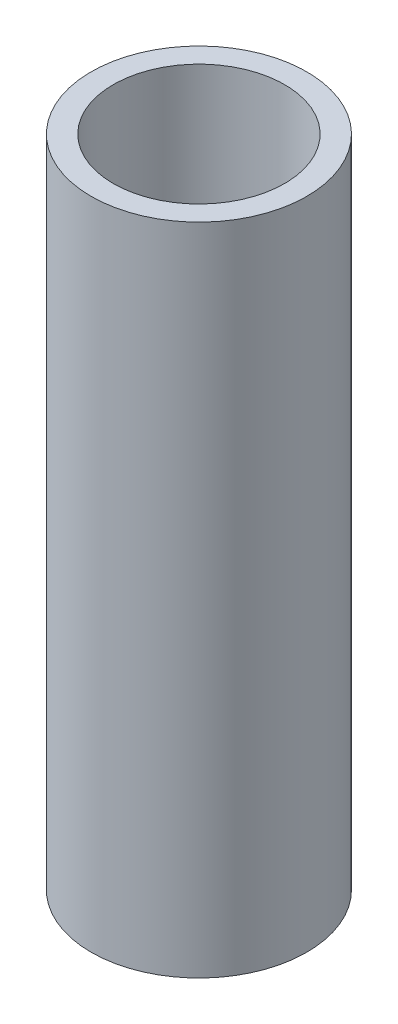
SolidWorks part; units mm, degrees
material "ABS"
ref_plane "Front Plane" through (0, 0, 0) normal (0, 0, 1) x (1, 0, 0)
ref_plane "Top Plane" through (0, 0, 0) normal (0, 1, 0) x (1, 0, 0)
ref_plane "Right Plane" through (0, 0, 0) normal (1, 0, 0) x (0, 0, -1)
sketch "Sketch1" plane through (0, 0, 0) normal (0, 1, 0) x (1, 0, 0)
  circle A0 centre (0, 0) radius 2.9972
  circle A1 centre (0, 0) radius 2.3813
  dimension "D1" = 5.9944
  dimension "D2" = 4.7625
extrude "Boss-Extrude1" add sketch "Sketch1" along normal mid plane 18.1898
